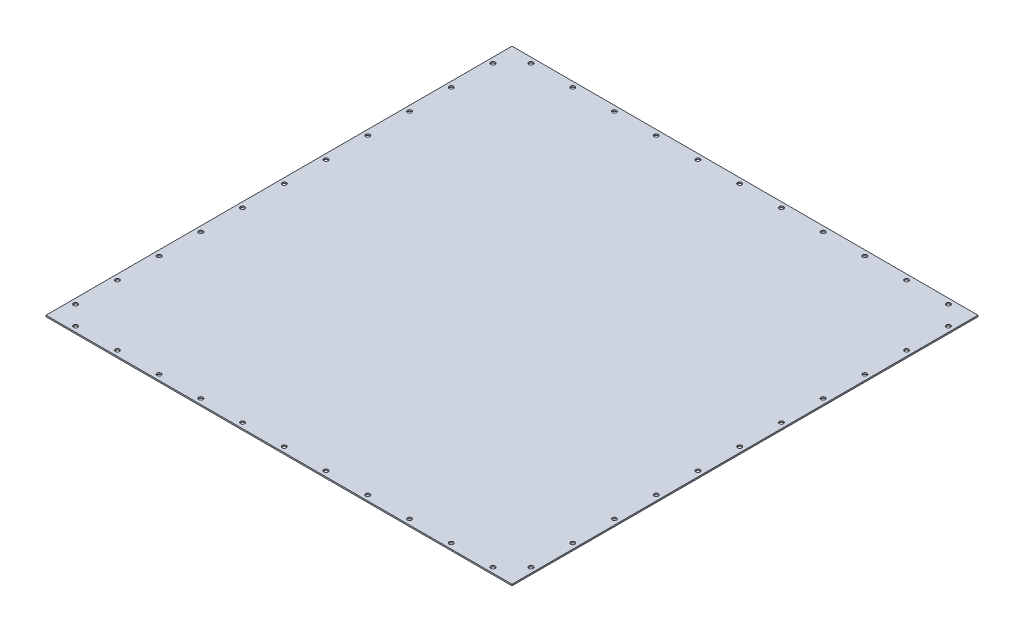
SolidWorks part; units mm, degrees
material "Acrylic (Medium-high impact)"
ref_plane "Front Plane" through (0, 0, 0) normal (0, 0, 1) x (1, 0, 0)
ref_plane "Top Plane" through (0, 0, 0) normal (0, 1, 0) x (1, 0, 0)
ref_plane "Right Plane" through (0, 0, 0) normal (1, 0, 0) x (0, 0, -1)
sketch "Sketch1" plane through (0, 0, 0) normal (0, 1, 0) x (1, 0, 0)
  line L0 (0, -809.2098) -> (0, 102.1407) construction
  line L1 (-658.75, 658.75) -> (658.75, 658.75)
  line L2 (-658.75, 658.75) -> (-658.75, -658.75)
  line L3 (-658.75, -658.75) -> (658.75, -658.75)
  line L4 (658.75, 658.75) -> (658.75, -658.75)
  line L5 (-658.75, 658.75) -> (658.75, -658.75) construction
  line L6 (-658.75, -658.75) -> (658.75, 658.75) construction
  line L7 (-744.8179, 0) -> (954.7326, 0) construction
  line L8 (643.75, 590) -> (643.75, 472) construction
  circle A0 centre (-590, -643.75) radius 6
  circle A1 centre (-472, -643.75) radius 6
  circle A2 centre (-354, -643.75) radius 6
  circle A3 centre (-236, -643.75) radius 6
  circle A4 centre (-118, -643.75) radius 6
  circle A5 centre (0, -643.75) radius 6
  circle A6 centre (118, -643.75) radius 6
  circle A7 centre (236, -643.75) radius 6
  circle A8 centre (354, -643.75) radius 6
  circle A9 centre (472, -643.75) radius 6
  circle A10 centre (590, -643.75) radius 6
  circle A11 centre (590, 643.75) radius 6
  circle A12 centre (472, 643.75) radius 6
  circle A13 centre (354, 643.75) radius 6
  circle A14 centre (236, 643.75) radius 6
  circle A15 centre (118, 643.75) radius 6
  circle A16 centre (0, 643.75) radius 6
  circle A17 centre (-118, 643.75) radius 6
  circle A18 centre (-236, 643.75) radius 6
  circle A19 centre (-354, 643.75) radius 6
  circle A20 centre (-472, 643.75) radius 6
  circle A21 centre (-590, 643.75) radius 6
  circle A22 centre (643.75, 590) radius 6
  circle A23 centre (643.75, 472) radius 6
  circle A24 centre (643.75, 354) radius 6
  circle A25 centre (643.75, 236) radius 6
  circle A26 centre (643.75, 118) radius 6
  circle A27 centre (643.75, 0) radius 6
  circle A28 centre (643.75, -118) radius 6
  circle A29 centre (643.75, -236) radius 6
  circle A30 centre (643.75, -354) radius 6
  circle A31 centre (643.75, -472) radius 6
  circle A32 centre (643.75, -590) radius 6
  circle A33 centre (-643.75, -590) radius 6
  circle A34 centre (-643.75, -472) radius 6
  circle A35 centre (-643.75, -354) radius 6
  circle A36 centre (-643.75, -236) radius 6
  circle A37 centre (-643.75, -118) radius 6
  circle A38 centre (-643.75, 0) radius 6
  circle A39 centre (-643.75, 118) radius 6
  circle A40 centre (-643.75, 236) radius 6
  circle A41 centre (-643.75, 354) radius 6
  circle A42 centre (-643.75, 472) radius 6
  circle A43 centre (-643.75, 590) radius 6
  point P0 (0, 0)
  dimension "D2" = 590
  dimension "D4" = 12
  dimension "D7" = 15
  dimension "D8" = 12
  dimension "D1" = 1317.5
  dimension "D3" = 15
  dimension "D5" = 590
  dimension "D9" = 590
  dimension "D11" = 118
  dimension "D6" = 11
  dimension "D10" = 11
extrude "Boss-Extrude1" add sketch "Sketch1" along normal mid plane 4
